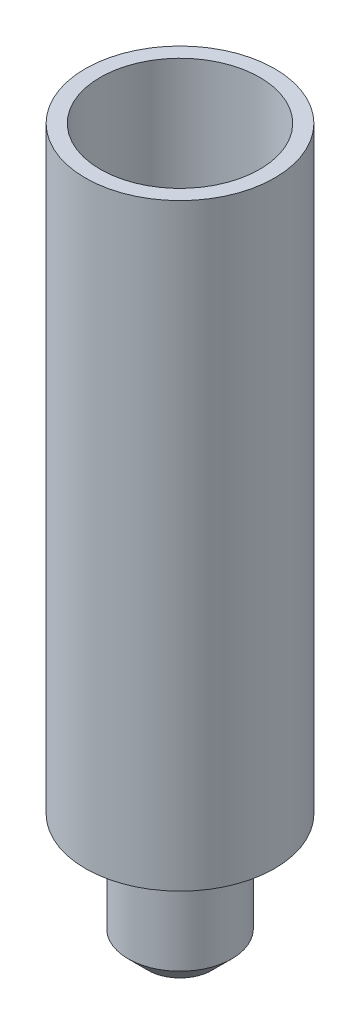
SolidWorks part; units mm, degrees
ref_plane "Front Plane" through (0, 0, 0) normal (0, 0, 1) x (1, 0, 0)
ref_plane "Top Plane" through (0, 0, 0) normal (0, 1, 0) x (1, 0, 0)
ref_plane "Right Plane" through (0, 0, 0) normal (1, 0, 0) x (0, 0, -1)
sketch "Sketch1" plane through (0, 0, 0) normal (0, 1, 0) x (1, 0, 0)
  circle A1 centre (0, 0) radius 2.6
  dimension "D2" = 5.2
extrude "Boss-Extrude1" add sketch "Sketch1" along normal blind 6 contours A1
sketch "Sketch2" plane through (0, 6, 0) normal (0, 1, 0) x (1, 0, 0)
  circle A1 centre (0, 0) radius 4.75
  dimension "D2" = 9.5
extrude "Boss-Extrude3" add sketch "Sketch2" along normal blind 2.5
sketch "Sketch3" plane through (0, 8.5, 0) normal (0, 1, 0) x (1, 0, 0)
  circle A0 centre (0, 0) radius 4.75
  circle A1 centre (0, 0) radius 4
  dimension "D1" = 8
extrude "Boss-Extrude4" add sketch "Sketch3" along normal blind 27.5
hole_wizard "M2 Tapped Hole1" positions "Sketch4" profile "Sketch5" tap size "M2" standard "GB" end condition up to next
sketch "Sketch4" plane through (0, 0, 0) normal (0, -1, 0) x (-1, 0, 0)
  point P0 (0, 0)
cosmetic thread "Hole Thread1"
sketch "Sketch5" plane through (0, 0, 0) normal (1, 0, 0) x (0, 0, -1)
  line L0 (0, 0) -> (0, 8.5)
  line L1 (0, 8.5) -> (0.8, 8.5)
  line L2 (0.8, 8.5) -> (0.8, 0.225)
  line L3 (0.8, 0.225) -> (1.025, 0)
  line L5 (1.025, 0) -> (0, 0)
  line L6 (-0.8, 0.225) -> (-1.025, 0) construction
  line L11 (0, -6.35) -> (0, 107.95) construction
  dimension "Thru Tap Drill Dia." = 1.6
  dimension "Thru Tap Drill Depth" = 8.5
  dimension "Near C'Sink Dia." = 2.05
  dimension "Near C'Sink Angle" = 90
chamfer "Chamfer3" distance 1 angle 45 1 edges at (0, 0, 2.6)
